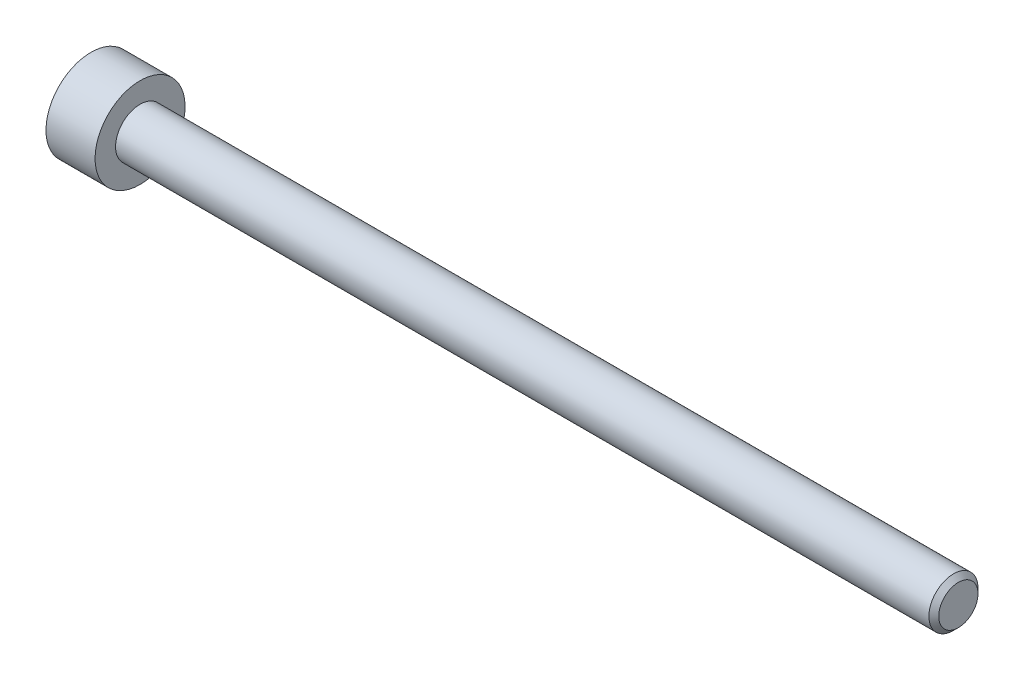
SolidWorks part; units mm, degrees
material "純碳鋼"
ref_plane "Front Plane" through (0, 0, 0) normal (0, 0, 1) x (1, 0, 0)
ref_plane "Top Plane" through (0, 0, 0) normal (0, 1, 0) x (1, 0, 0)
ref_plane "Right Plane" through (0, 0, 0) normal (1, 0, 0) x (0, 0, -1)
sketch "Sketch2" plane through (0, 0, 0) normal (1, 0, 0) x (0, 0, -1)
  circle A0 centre (0, 0) radius 1.5
  dimension "D1" = 3
extrude "Boss-Extrude1" add sketch "Sketch2" against normal blind 50
chamfer "Chamfer1" distance 0.3 angle 45 1 edges at (0, 0, -1.5)
sketch "Sketch6" plane through (0, 0, 0) normal (0, 0, 1) x (1, 0, 0)
  line L0 (-53, 0) -> (-53, 2.75)
  line L1 (-53, 0) -> (-50, 0)
  line L2 (-53, 2.75) -> (-50, 2.75)
  line L6 (-50, 2.75) -> (-50, 0)
  line L8 (-50, 0) -> (-14.6471, 0) construction
  line L10 (-50, 1.5) -> (-50, -1.5) construction
  dimension "D1" = 3
  dimension "D2" = 5.5
revolve "Revolve1" add sketch "Sketch6" angle 360 about L8
sketch "Sketch7" plane through (-53, 0, 0) normal (-1, 0, 0) x (0, 0, 1)
  line L1 (0, 1.4434) -> (-1.25, 0.7217)
  line L2 (-1.25, 0.7217) -> (-1.25, -0.7217)
  line L3 (-1.25, -0.7217) -> (0, -1.4434)
  line L4 (0, -1.4434) -> (1.25, -0.7217)
  line L5 (1.25, -0.7217) -> (1.25, 0.7217)
  line L6 (1.25, 0.7217) -> (0, 1.4434)
  circle A0 centre (0, 0) radius 1.25 construction
  dimension "D1" = 2.5
extrude "Cut-Extrude1" cut sketch "Sketch7" against normal blind 1.6
sketch "Sketch8" plane through (-53, 0, 0) normal (-1, 0, 0) x (0, 0, 1)
  circle A0 centre (0, 0) radius 1.4934
  dimension "D1" = 0.05
extrude "Cut-Extrude2" cut sketch "Sketch8" against normal blind 1 draft 45
